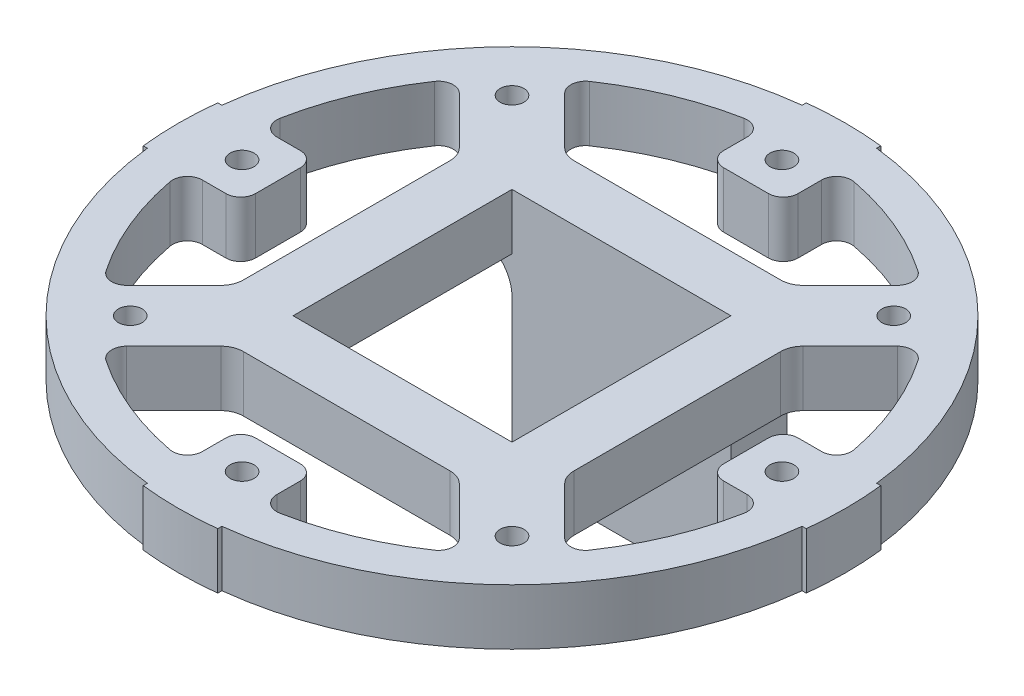
SolidWorks part; units mm, degrees
ref_plane "Front Plane" through (0, 0, 0) normal (0, 0, 1) x (1, 0, 0)
ref_plane "Top Plane" through (0, 0, 0) normal (0, 1, 0) x (1, 0, 0)
ref_plane "Right Plane" through (0, 0, 0) normal (1, 0, 0) x (0, 0, -1)
sketch "Sketch1" plane through (0, 0, 0) normal (0, 1, 0) x (1, 0, 0)
  line L0 (0, 0) -> (44.25, 0) construction
  line L1 (33.4302, 5) -> (36.5864, 5)
  line L2 (33.4302, -5) -> (36.5864, -5)
  line L3 (31.4302, 3) -> (31.4302, -3)
  line L4 (25.7601, -18.689) -> (29.406, -22.3349)
  line L5 (25.7601, -18.689) -> (18.689, -25.7601)
  line L6 (18.689, -25.7601) -> (22.3349, -29.406)
  line L7 (5, -33.4302) -> (5, -36.5864)
  line L8 (3, -31.4302) -> (-3, -31.4302)
  line L9 (-5, -33.4302) -> (-5, -36.5864)
  line L10 (-18.689, -25.7601) -> (-22.3349, -29.406)
  line L11 (-18.689, -25.7601) -> (-25.7601, -18.689)
  line L12 (-25.7601, -18.689) -> (-29.406, -22.3349)
  line L13 (-33.4302, -5) -> (-36.5864, -5)
  line L14 (-31.4302, -3) -> (-31.4302, 3)
  line L15 (-33.4302, 5) -> (-36.5864, 5)
  line L16 (-25.7601, 18.689) -> (-29.406, 22.3349)
  line L17 (-25.7601, 18.689) -> (-18.689, 25.7601)
  line L18 (-18.689, 25.7601) -> (-22.3349, 29.406)
  line L19 (-5, 33.4302) -> (-5, 36.5864)
  line L20 (-3, 31.4302) -> (3, 31.4302)
  line L21 (5, 33.4302) -> (5, 36.5864)
  line L22 (18.689, 25.7601) -> (22.3349, 29.406)
  line L23 (18.689, 25.7601) -> (25.7601, 18.689)
  line L24 (25.7601, 18.689) -> (29.406, 22.3349)
  line L25 (-5, 38.9302) -> (-5, 46.441) construction
  line L26 (5, 38.9302) -> (5, 47.4442) construction
  line L27 (-5, 43.9666) -> (-5, 44.5201)
  line L28 (5, 43.9666) -> (5, 44.5201)
  line L29 (43.9666, -5) -> (44.5201, -5)
  line L30 (43.9666, 5) -> (44.5201, 5)
  line L31 (-5, -43.9666) -> (-5, -44.5201)
  line L32 (5, -43.9666) -> (5, -44.5201)
  line L33 (-43.9666, 5) -> (-44.5201, 5)
  line L34 (-43.9666, -5) -> (-44.5201, -5)
  arc A0 (-43.9666, -5) -> (-5, -43.9666) centre (0, 0) ccw
  circle A1 centre (0, 0) radius 36.25 construction
  circle A2 centre (36.25, 0) radius 1.6
  arc A3 (38.5507, 7.3758) -> (32.475, 22.044) centre (0, 0) ccw
  circle A4 centre (25.6326, -25.6326) radius 1.6
  circle A5 centre (0, -36.25) radius 1.6
  circle A6 centre (-25.6326, -25.6326) radius 1.6
  circle A7 centre (-36.25, 0) radius 1.6
  circle A8 centre (-25.6326, 25.6326) radius 1.6
  circle A9 centre (0, 36.25) radius 1.6
  circle A10 centre (25.6326, 25.6326) radius 1.6
  arc A11 (-7.3758, 38.5507) -> (-22.044, 32.475) centre (0, 0) ccw
  arc A12 (22.044, 32.475) -> (7.3758, 38.5507) centre (0, 0) ccw
  arc A13 (-32.475, 22.044) -> (-38.5507, 7.3758) centre (0, 0) ccw
  arc A14 (-38.5507, -7.3758) -> (-32.475, -22.044) centre (0, 0) ccw
  arc A15 (-22.044, -32.475) -> (-7.3758, -38.5507) centre (0, 0) ccw
  arc A16 (7.3758, -38.5507) -> (22.044, -32.475) centre (0, 0) ccw
  arc A17 (32.475, -22.044) -> (38.5507, -7.3758) centre (0, 0) ccw
  arc A18 (-44.5201, 5) -> (-44.5201, -5) centre (0, 0) ccw
  arc A19 (-5, -44.5201) -> (5, -44.5201) centre (0, 0) ccw
  arc A20 (-5, 43.9666) -> (-43.9666, 5) centre (0, 0) ccw
  arc A21 (5, 44.5201) -> (-5, 44.5201) centre (0, 0) ccw
  arc A22 (43.9666, 5) -> (5, 43.9666) centre (0, 0) ccw
  arc A23 (44.5201, -5) -> (44.5201, 5) centre (0, 0) ccw
  arc A24 (5, -43.9666) -> (43.9666, -5) centre (0, 0) ccw
  arc A25 (-36.5864, 5) -> (-38.5507, 7.3758) centre (-36.5864, 7) cw
  arc A26 (-36.5864, -5) -> (-38.5507, -7.3758) centre (-36.5864, -7) ccw
  arc A27 (-29.406, -22.3349) -> (-32.475, -22.044) centre (-30.8202, -20.9207) cw
  arc A28 (-22.3349, -29.406) -> (-22.044, -32.475) centre (-20.9207, -30.8202) ccw
  arc A29 (-5, -36.5864) -> (-7.3758, -38.5507) centre (-7, -36.5864) cw
  arc A30 (5, -36.5864) -> (7.3758, -38.5507) centre (7, -36.5864) ccw
  arc A31 (22.3349, -29.406) -> (22.044, -32.475) centre (20.9207, -30.8202) cw
  arc A32 (29.406, -22.3349) -> (32.475, -22.044) centre (30.8202, -20.9207) ccw
  arc A33 (36.5864, -5) -> (38.5507, -7.3758) centre (36.5864, -7) cw
  arc A34 (36.5864, 5) -> (38.5507, 7.3758) centre (36.5864, 7) ccw
  arc A35 (29.406, 22.3349) -> (32.475, 22.044) centre (30.8202, 20.9207) cw
  arc A36 (22.3349, 29.406) -> (22.044, 32.475) centre (20.9207, 30.8202) ccw
  arc A37 (5, 36.5864) -> (7.3758, 38.5507) centre (7, 36.5864) cw
  arc A38 (-5, 36.5864) -> (-7.3758, 38.5507) centre (-7, 36.5864) ccw
  arc A39 (-22.3349, 29.406) -> (-22.044, 32.475) centre (-20.9207, 30.8202) cw
  arc A40 (-29.406, 22.3349) -> (-32.475, 22.044) centre (-30.8202, 20.9207) ccw
  arc A41 (3, 31.4302) -> (5, 33.4302) centre (3, 33.4302) ccw
  arc A42 (-5, 33.4302) -> (-3, 31.4302) centre (-3, 33.4302) ccw
  arc A43 (33.4302, 5) -> (31.4302, 3) centre (33.4302, 3) ccw
  arc A44 (33.4302, -5) -> (31.4302, -3) centre (33.4302, -3) cw
  arc A45 (5, -33.4302) -> (3, -31.4302) centre (3, -33.4302) ccw
  arc A46 (-3, -31.4302) -> (-5, -33.4302) centre (-3, -33.4302) ccw
  arc A47 (-33.4302, -5) -> (-31.4302, -3) centre (-33.4302, -3) ccw
  arc A48 (-31.4302, 3) -> (-33.4302, 5) centre (-33.4302, 3) ccw
  point P55 (0, 0)
  point P76 (0, 0)
  point P90 (38.9302, -5)
  point P93 (38.9302, 5)
  point P114 (31.4302, 5)
  point P117 (31.4302, -5)
  dimension "D1" = 88.5
  dimension "D2" = 72.5
  dimension "D3" = 3.2
  dimension "D4" = 5
  dimension "D8" = 89.6
  dimension "D10" = 2
  dimension "D11" = 2
  dimension "D5" = 7.5
  dimension "D6" = 10
  dimension "D7" = 8
  dimension "D9" = 4
extrude "Boss-Extrude1" add sketch "Sketch1" along normal blind 7.5
sketch "Sketch2" plane through (0, 7.5, 0) normal (0, 1, 0) x (1, 0, 0)
  line L0 (25.7601, 18.689) -> (18.689, 25.7601) construction
  line L1 (13.8863, 22.2) -> (-13.8863, 22.2)
  line L2 (-22.2, 13.8863) -> (-22.2, -13.8863)
  line L3 (-13.8863, -22.2) -> (13.8863, -22.2)
  line L4 (22.2, -13.8863) -> (22.2, 13.8863)
  line L5 (18.689, -25.7601) -> (25.7601, -18.689) construction
  line L6 (-25.7601, -18.689) -> (-18.689, -25.7601) construction
  line L7 (-18.689, 25.7601) -> (-25.7601, 18.689) construction
  line L8 (25.7601, 18.689) -> (18.689, 25.7601)
  line L9 (18.689, -25.7601) -> (25.7601, -18.689)
  line L10 (-25.7601, -18.689) -> (-18.689, -25.7601)
  line L11 (-18.689, 25.7601) -> (-25.7601, 18.689)
  line L12 (-25.7601, 18.689) -> (-23.0787, 16.0076)
  line L13 (-18.689, 25.7601) -> (-16.0076, 23.0787)
  line L14 (18.689, 25.7601) -> (16.0076, 23.0787)
  line L15 (25.7601, 18.689) -> (23.0787, 16.0076)
  line L16 (25.7601, -18.689) -> (23.0787, -16.0076)
  line L17 (18.689, -25.7601) -> (16.0076, -23.0787)
  line L18 (-25.7601, -18.689) -> (-23.0787, -16.0076)
  line L19 (-18.689, -25.7601) -> (-16.0076, -23.0787)
  line L21 (-14.7, 14.7) -> (-14.7, -14.7)
  line L22 (-14.7, -14.7) -> (14.7, -14.7)
  line L23 (14.7, -14.7) -> (14.7, 14.7)
  line L24 (14.7, 14.7) -> (-14.7, 14.7)
  circle A0 centre (0, 0) radius 14.7 construction
  circle A1 centre (0, 0) radius 22.2 construction
  arc A2 (16.0076, 23.0787) -> (13.8863, 22.2) centre (13.8863, 25.2) cw
  arc A3 (23.0787, 16.0076) -> (22.2, 13.8863) centre (25.2, 13.8863) ccw
  arc A4 (23.0787, -16.0076) -> (22.2, -13.8863) centre (25.2, -13.8863) cw
  arc A5 (16.0076, -23.0787) -> (13.8863, -22.2) centre (13.8863, -25.2) ccw
  arc A6 (-16.0076, -23.0787) -> (-13.8863, -22.2) centre (-13.8863, -25.2) cw
  arc A7 (-23.0787, -16.0076) -> (-22.2, -13.8863) centre (-25.2, -13.8863) ccw
  arc A8 (-23.0787, 16.0076) -> (-22.2, 13.8863) centre (-25.2, 13.8863) cw
  arc A9 (-16.0076, 23.0787) -> (-13.8863, 22.2) centre (-13.8863, 25.2) ccw
  dimension "D1" = 29.4
  dimension "D2" = 7.5
  dimension "D3" = 3
extrude "Boss-Extrude2" add sketch "Sketch2" against normal blind 7.5
sketch "Sketch3" plane through (0, 0, -14.7) normal (0, 0, 1) x (1, 0, 0)
  line L0 (-14.7, 5.5) -> (14.7, 5.5)
  line L1 (-14.7, 5.5) -> (-14.7, -25.5)
  line L2 (14.7, 5.5) -> (14.7, -25.5)
  line L3 (-14.7, -25.5) -> (14.7, -25.5)
  line L4 (-14.7, 0) -> (-14.7, 7.5) construction
  line L5 (14.7, 0) -> (14.7, 7.5) construction
  line L6 (14.7, 7.5) -> (-14.7, 7.5) construction
  line L7 (0, 0) -> (0, -29.1717) construction
  circle A0 centre (-12, -21.5) radius 1.6
  circle A1 centre (12, -21.5) radius 1.6
  dimension "D3" = 3.2
  dimension "D1" = 2
  dimension "D2" = 31
  dimension "D4" = 4
  dimension "D5" = 24
extrude "Boss-Extrude3" add sketch "Sketch3" against normal up to surface (7.5 mm away) up to face at (0, 3.75, -22.2)
fillet "Fillet1" radius 5 2 edges at (14.7, 0, -18.45) (-14.7, 0, -18.45)
fillet "Fillet2" radius 2 2 edges at (-14.7, -25.5, -18.45) (14.7, -25.5, -18.45)
